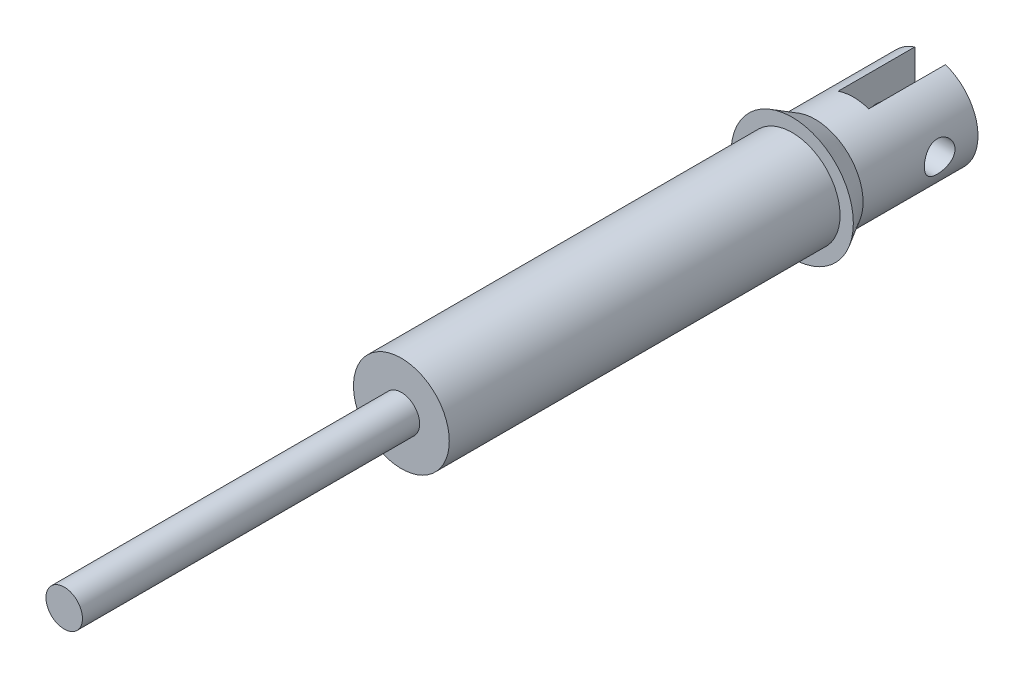
SolidWorks part; units mm, degrees
ref_plane "Front" through (0, 0, 0) normal (0, 0, 1) x (1, 0, 0)
ref_plane "Top" through (0, 0, 0) normal (0, 1, 0) x (1, 0, 0)
ref_plane "Right" through (0, 0, 0) normal (1, 0, 0) x (0, 0, -1)
sketch "Sketch1" plane through (0, 0, 0) normal (0, 0, 1) x (1, 0, 0)
  circle A0 centre (0, 0) radius 6.25
  dimension "D1" = 12.5
extrude "Boss-Extrude1" add sketch "Sketch1" along normal blind 15
sketch "Sketch2" plane through (0, 0, 15) normal (0, 0, 1) x (1, 0, 0)
  circle A0 centre (0, 0) radius 6.25
extrude "Boss-Extrude2" add sketch "Sketch2" along normal blind 3 draft 30 draft outward yes
sketch "Sketch3" plane through (0, 0, 18) normal (0, 0, 1) x (1, 0, 0)
  circle A0 centre (0, 0) radius 6.25
  dimension "D1" = 12.5
extrude "Boss-Extrude3" add sketch "Sketch3" along normal blind 51
sketch "Sketch4" plane through (0, 0, 69) normal (0, 0, 1) x (1, 0, 0)
  circle A0 centre (0, 0) radius 2.3812
  dimension "D1" = 4.7625
extrude "Boss-Extrude4" add sketch "Sketch4" along normal blind 44
sketch "Sketch5" plane through (0, 0, 0) normal (0, 0, -1) x (-1, 0, 0)
  line L1 (-2, 7.8039) -> (2, 7.8039)
  line L2 (-2, 7.8039) -> (-2, -7.1371)
  line L3 (-2, -7.1371) -> (2, -7.1371)
  line L4 (2, 7.8039) -> (2, -7.1371)
  circle A0 centre (0, 0) radius 6.25 construction
  dimension "D1" = 2
  dimension "D2" = 4
extrude "Cut-Extrude1" cut sketch "Sketch5" against normal blind 10
sketch "Sketch6" plane through (2, 0, 0) normal (-1, 0, 0) x (0, 0, 1)
  line L0 (0, 0) -> (10.2941, 0) construction
  line L1 (0, -5.9214) -> (0, 5.9214) construction
  circle A0 centre (5, 0) radius 2
  dimension "D1" = 5
  dimension "D2" = 4
extrude "Cut-Extrude2" cut sketch "Sketch6" against normal through all and the other way through all
